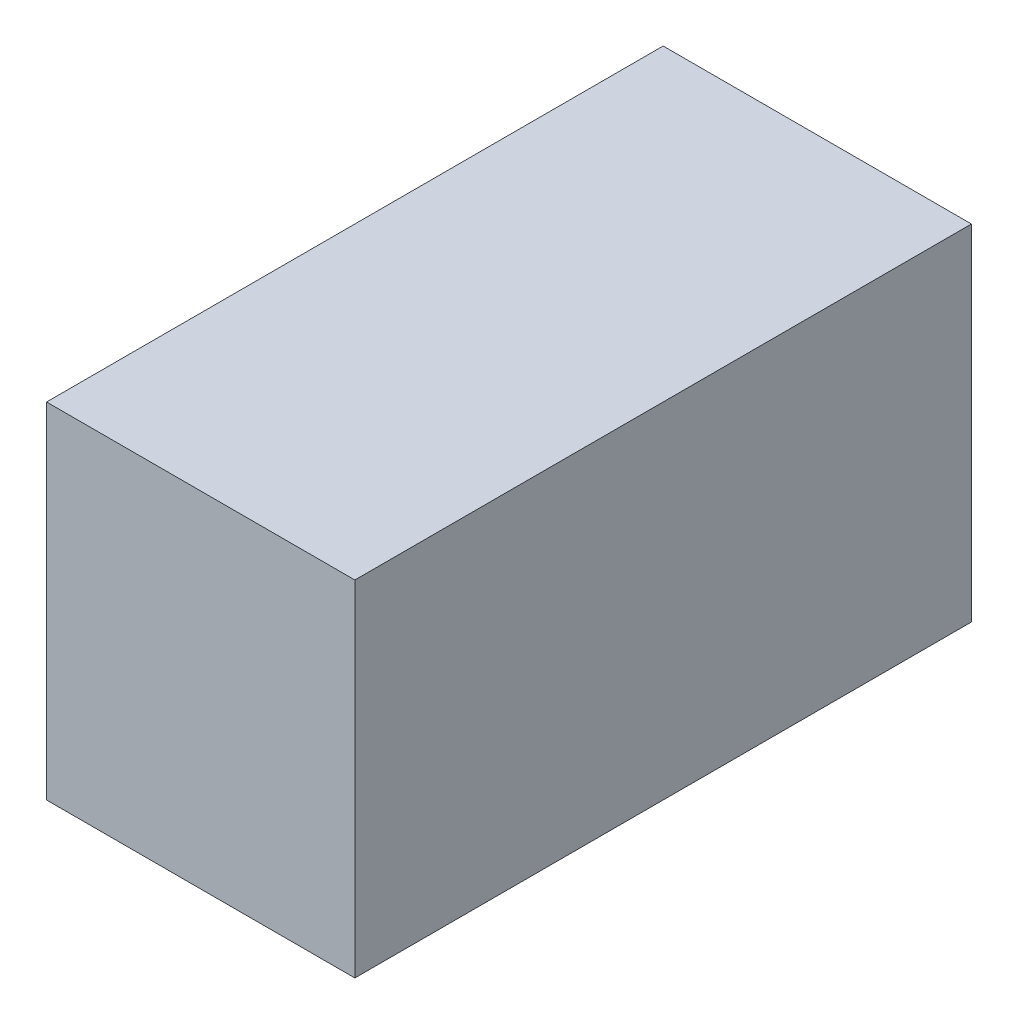
SolidWorks part; units mm, degrees
ref_plane "Front Plane" through (0, 0, 0) normal (0, 0, 1) x (1, 0, 0)
ref_plane "Top Plane" through (0, 0, 0) normal (0, 1, 0) x (1, 0, 0)
ref_plane "Right Plane" through (0, 0, 0) normal (1, 0, 0) x (0, 0, -1)
sketch "Sketch1" plane through (0, 0, 0) normal (0, 1, 0) x (1, 0, 0)
  line L1 (-25.4, 50.8) -> (25.4, 50.8)
  line L2 (-25.4, 50.8) -> (-25.4, -50.8)
  line L3 (-25.4, -50.8) -> (25.4, -50.8)
  line L4 (25.4, 50.8) -> (25.4, -50.8)
  line L5 (-25.4, 50.8) -> (25.4, -50.8) construction
  line L6 (-25.4, -50.8) -> (25.4, 50.8) construction
  point P0 (0, 0)
  dimension "D1" = 50.8
  dimension "D2" = 101.6
extrude "Boss-Extrude1" add sketch "Sketch1" along normal mid plane 56.8
